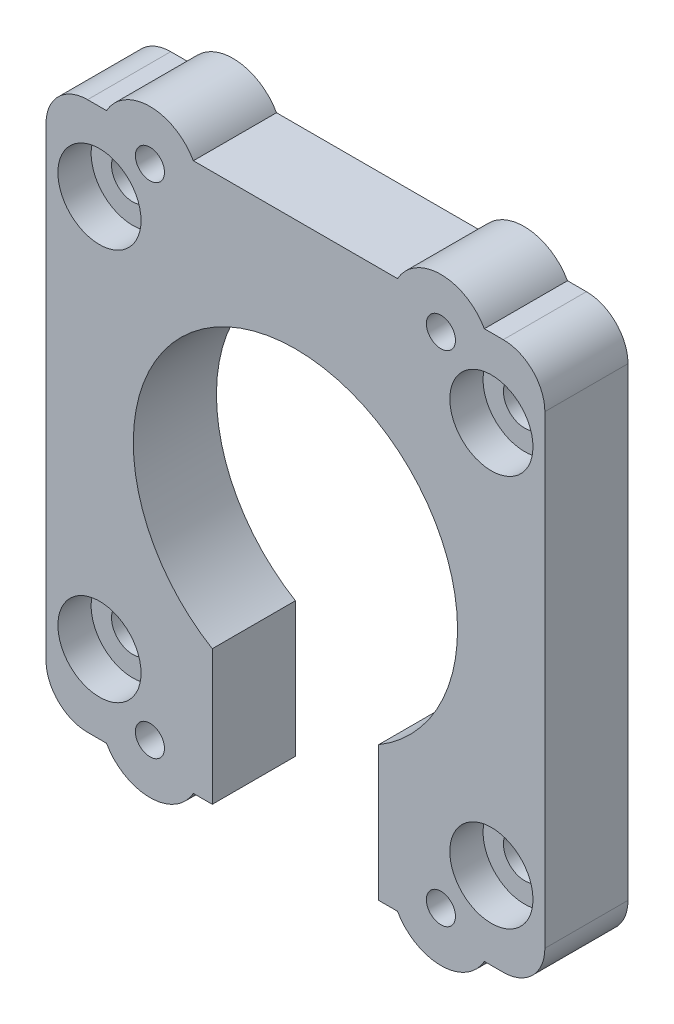
SolidWorks part; units mm, degrees
ref_plane "Plano frontal" through (0, 0, 0) normal (0, 0, 1) x (1, 0, 0)
ref_plane "Plano superior" through (0, 0, 0) normal (0, 1, 0) x (1, 0, 0)
ref_plane "Plano direito" through (0, 0, 0) normal (1, 0, 0) x (0, 0, -1)
sketch "Esboço1" plane through (0, 0, 0) normal (0, 0, 1) x (1, 0, 0)
  line L1 (25, -32.9508) -> (-25, -32.9508)
  line L2 (30, -27.9508) -> (30, 27.9508)
  line L3 (25, 32.9508) -> (-25, 32.9508)
  line L4 (-30, -27.9508) -> (-30, 27.9508)
  line L5 (30, -32.9508) -> (-30, 32.9508) construction
  line L6 (30, 32.9508) -> (-30, -32.9508) construction
  arc A0 (-25, -32.9508) -> (-30, -27.9508) centre (-25, -27.9508) cw
  arc A1 (25, -32.9508) -> (30, -27.9508) centre (25, -27.9508) ccw
  arc A2 (30, 27.9508) -> (25, 32.9508) centre (25, 27.9508) ccw
  arc A3 (-25, 32.9508) -> (-30, 27.9508) centre (-25, 27.9508) ccw
  circle A4 centre (0, 0) radius 42.5 construction
  point P0 (0, 0)
  dimension "D3" = 5
  dimension "D4" = 85
  dimension "D1" = 60
extrude "Ressalto-extrusão1" add sketch "Esboço1" along normal blind 10
sketch "Esboço2" plane through (0, 0, 10) normal (0, 0, 1) x (1, 0, 0)
  line L1 (23.57, -23.57) -> (-23.57, -23.57) construction
  line L2 (23.57, -23.57) -> (23.57, 23.57) construction
  line L3 (23.57, 23.57) -> (-23.57, 23.57) construction
  line L4 (-23.57, -23.57) -> (-23.57, 23.57) construction
  line L5 (23.57, -23.57) -> (-23.57, 23.57) construction
  line L6 (23.57, 23.57) -> (-23.57, -23.57) construction
  circle A0 centre (-23.57, 23.57) radius 2.55
  circle A1 centre (23.57, 23.57) radius 2.55
  circle A2 centre (23.57, -23.57) radius 2.55
  circle A3 centre (-23.57, -23.57) radius 2.55
  point P0 (0, 0)
  dimension "D2" = 5.1
  dimension "D1" = 47.14
extrude "Corte-extrusão1" cut sketch "Esboço2" against normal blind 10
sketch "Esboço4" plane through (0, 0, 10) normal (0, 0, 1) x (1, 0, 0)
  circle A0 centre (0, 0) radius 19.5
  dimension "D1" = 39
extrude "Corte-extrusão3" cut sketch "Esboço4" against normal blind 10
sketch "Esboço5" plane through (0, -32.9508, 0) normal (0, -1, 0) x (1, 0, 0)
  line L0 (-25, 0) -> (25, 0) construction
  line L1 (10, 10) -> (-10, 10)
  line L2 (10, 10) -> (10, 0)
  line L3 (10, 0) -> (-10, 0)
  line L4 (-10, 10) -> (-10, 0)
  line L5 (10, 10) -> (-10, 0) construction
  line L6 (10, 0) -> (-10, 10) construction
  line L7 (-25, 10) -> (25, 10) construction
  point P0 (0, 5)
  dimension "D1" = 20
extrude "Corte-extrusão4" cut sketch "Esboço5" against normal blind 30
sketch "Esboço6" plane through (0, 0, 0) normal (0, 0, -1) x (-1, 0, 0)
  line L1 (17.5, -30) -> (-17.5, -30) construction
  line L2 (17.5, -30) -> (17.5, 30) construction
  line L3 (17.5, 30) -> (-17.5, 30) construction
  line L4 (-17.5, -30) -> (-17.5, 30) construction
  line L5 (17.5, -30) -> (-17.5, 30) construction
  line L6 (17.5, 30) -> (-17.5, -30) construction
  circle A0 centre (17.5, 30) radius 1.75
  circle A1 centre (-17.5, 30) radius 1.75
  circle A2 centre (-17.5, -30) radius 1.75
  circle A3 centre (17.5, -30) radius 1.75
  point P0 (0, 0)
  dimension "D3" = 3.5
  dimension "D1" = 60
  dimension "D2" = 35
extrude "Corte-extrusão5" cut sketch "Esboço6" against normal blind 10
sketch "Esboço7" plane through (0, 0, 0) normal (0, 0, -1) x (-1, 0, 0)
  circle A0 centre (17.5, -30) radius 6
  circle A1 centre (-17.5, -30) radius 6
  circle A2 centre (-17.5, 30) radius 6
  circle A3 centre (17.5, 30) radius 6
  circle A4 centre (-17.5, 30) radius 1.75 construction
  circle A5 centre (-17.5, 30) radius 1.75
  circle A6 centre (-17.5, -30) radius 1.75 construction
  circle A7 centre (17.5, -30) radius 1.75 construction
  circle A8 centre (17.5, 30) radius 1.75 construction
  circle A9 centre (-17.5, -30) radius 1.75
  circle A10 centre (17.5, -30) radius 1.75
  circle A11 centre (17.5, 30) radius 1.75
  dimension "D1" = 12
extrude "Ressalto-extrusão2" add sketch "Esboço7" against normal blind 10
sketch "Esboço9" plane through (0, 0, 10) normal (0, 0, 1) x (1, 0, 0)
  circle A0 centre (23.57, 23.57) radius 5
  circle A1 centre (-23.57, 23.57) radius 5
  circle A2 centre (23.57, -23.57) radius 5
  circle A3 centre (-23.57, -23.57) radius 5
  dimension "D1" = 10
extrude "Corte-extrusão6" cut sketch "Esboço9" against normal blind 4
sketch "Esboço10" plane through (0, 0, 0) normal (0, 0, -1) x (-1, 0, 0)
  circle A0 centre (-17.5, -30) radius 3.5
  circle A1 centre (17.5, -30) radius 3.5
  circle A2 centre (17.5, 30) radius 3.5
  circle A3 centre (-17.5, 30) radius 3.5
  dimension "D1" = 7
extrude "Corte-extrusão7" cut sketch "Esboço10" against normal blind 4
